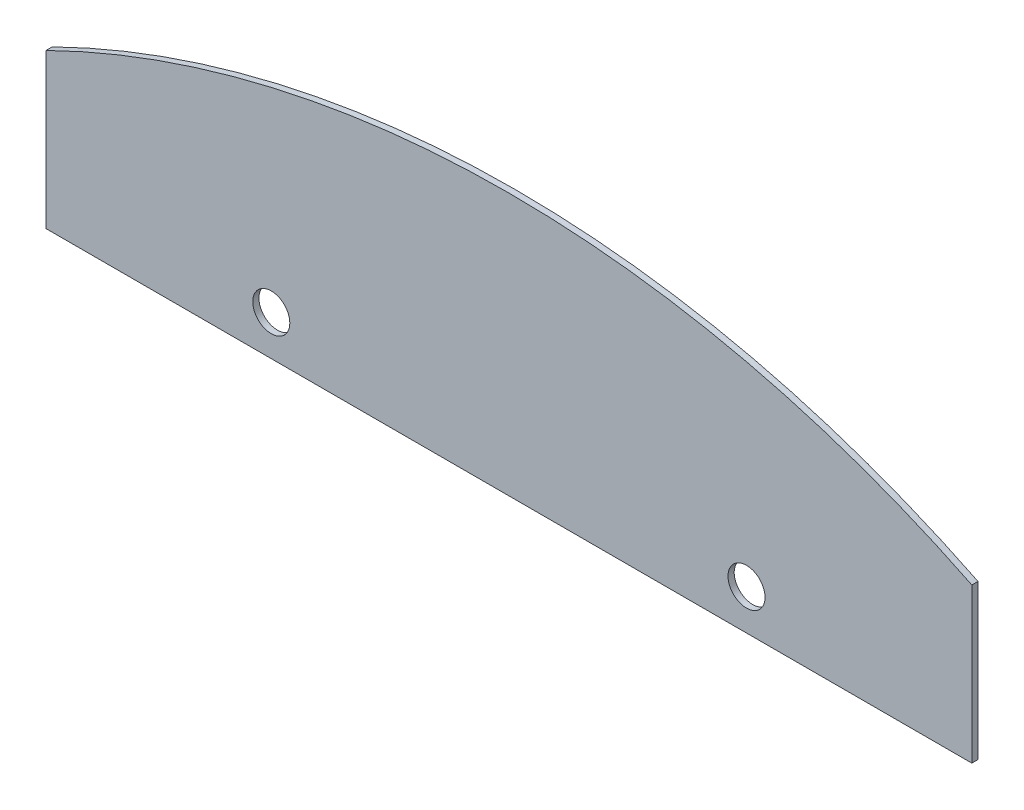
SolidWorks part; units mm, degrees
ref_plane "Alzado" through (0, 0, 0) normal (0, 0, 1) x (1, 0, 0)
ref_plane "Planta" through (0, 0, 0) normal (0, 1, 0) x (1, 0, 0)
ref_plane "Vista lateral" through (0, 0, 0) normal (1, 0, 0) x (0, 0, -1)
sketch "Croquis1" plane through (0, 0, 0) normal (0, 0, 1) x (1, 0, 0)
  line L0 (-150, 0) -> (150, 0)
  line L1 (150, 0) -> (150, 50)
  line L2 (-150, 0) -> (-150, 50)
  arc A0 (150, 50) -> (-150, 50) centre (0, -253.9286) ccw
  point P7 (0, 85)
  dimension "D1" = 50
  dimension "D2" = 300
  dimension "D3" = 150
  dimension "D4" = 85
  dimension "D5" = 50
extrude "Saliente-Extruir1" add sketch "Croquis1" along normal blind 2
sketch "Croquis2" plane through (0, 0, 2) normal (0, 0, 1) x (1, 0, 0)
  line L0 (-150, 50) -> (-150, 0) construction
  line L1 (-150, 0) -> (150, 0) construction
  line L2 (150, 0) -> (150, 50) construction
  circle A0 centre (-77, 13) radius 6
  circle A1 centre (77, 13) radius 6
  dimension "D1" = 12
  dimension "D2" = 73
  dimension "D3" = 13
  dimension "D4" = 12
  dimension "D5" = 73
  dimension "D6" = 13
extrude "Cortar-Extruir1" cut sketch "Croquis2" against normal through all
